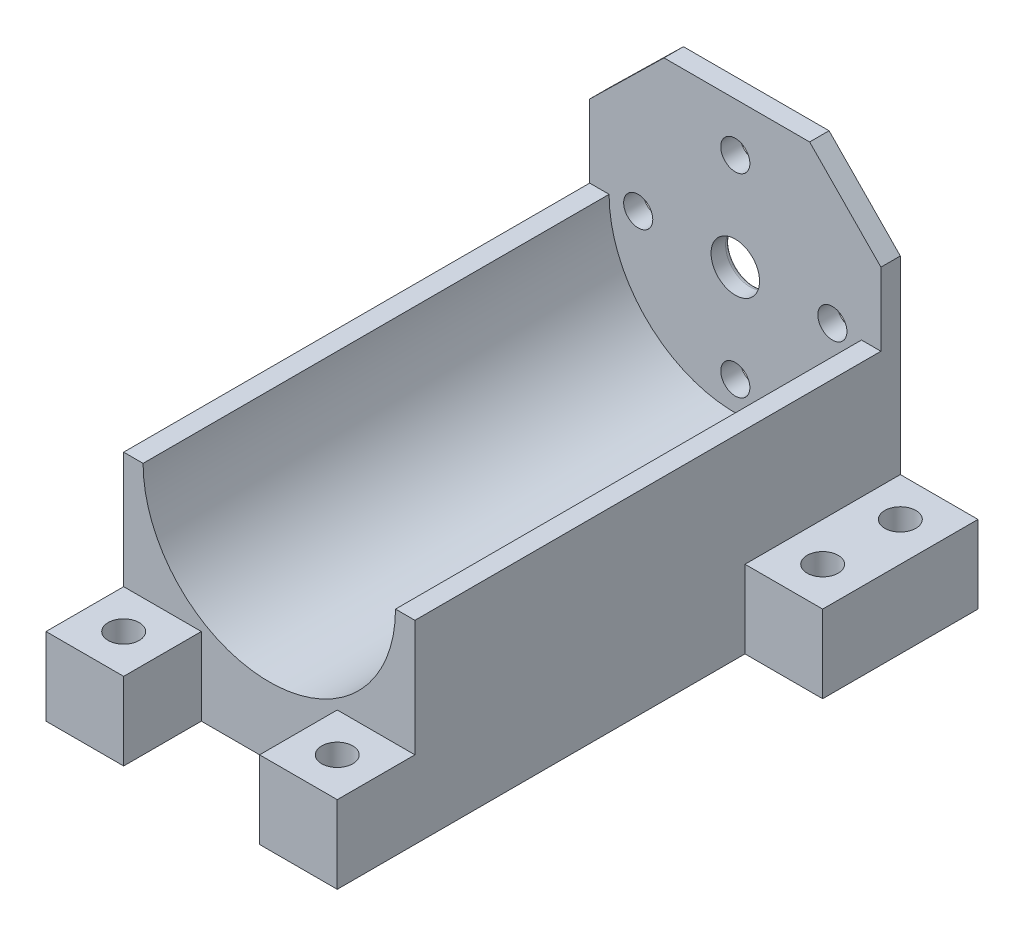
SolidWorks part; units mm, degrees
ref_plane "Plan de face" through (0, 0, 0) normal (0, 0, 1) x (1, 0, 0)
ref_plane "Plan de dessus" through (0, 0, 0) normal (0, 1, 0) x (1, 0, 0)
ref_plane "Plan de droite" through (0, 0, 0) normal (1, 0, 0) x (0, 0, -1)
sketch "Esquisse1" plane through (0, 0, 0) normal (0, 0, 1) x (1, 0, 0)
  line L0 (0, 0) -> (0, 10) construction
  line L1 (0, 0) -> (10, 0) construction
  line L2 (0, 0) -> (0, -10) construction
  line L3 (0, 0) -> (-10, 0) construction
  line L4 (-15, 0) -> (-15, 15)
  line L5 (-15, 15) -> (15, 15)
  line L6 (15, 15) -> (15, 0)
  line L7 (-15, 0) -> (-13, 0)
  line L8 (15, 0) -> (13, 0)
  line L9 (-15, 15) -> (-15, 0)
  line L10 (-15, 15) -> (0.318, 15)
  line L11 (-15, 15) -> (-15, 0)
  line L12 (-15, 7.5) -> (-15, 15)
  line L13 (-15, 15) -> (-7.341, 15)
  line L14 (-15, 7.5) -> (-7.341, 15)
  line L15 (15, 15) -> (15, 0)
  line L16 (15, 7.5) -> (15, 15)
  line L17 (0.318, 15) -> (15, 15)
  line L18 (7.659, 15) -> (15, 15)
  line L19 (7.659, 15) -> (15, 7.5)
  circle A0 centre (0, 0) radius 13
  circle A1 centre (0, 0) radius 15
  circle A2 centre (0, 10) radius 1.5
  circle A3 centre (-10, 0) radius 1.5
  circle A4 centre (10, 0) radius 1.5
  circle A5 centre (0, -10) radius 1.5
  circle A6 centre (0, 0) radius 2.5
  arc A7 (-13, 0) -> (13, 0) centre (0, 0) cw
extrude "Boss.-Extru.1" add sketch "Esquisse1" along normal blind 2 contours A0 A6 A5 A4 A3 A2 | L8 A1 L7 A0 | A1 L5 L4 | A1 L6 L5
sketch "Esquisse2" plane through (0, 0, 0) normal (0, 0, -1) x (-1, 0, 0)
  line L0 (0, 0) -> (0, -20) construction
  line L1 (0, -20) -> (15, -20)
  line L2 (15, -20) -> (15, 0)
  line L3 (0, -20) -> (-15, -20)
  line L4 (-15, -20) -> (-15, 0)
  line L5 (-15, 0) -> (-13, 0)
  line L6 (15, 0) -> (13, 0)
  line L7 (-15, 0) -> (-15, 15)
  line L8 (-15, 15) -> (15, 15)
  line L9 (15, 15) -> (15, 0)
  circle A0 centre (0, 0) radius 15
  circle A1 centre (0, 0) radius 13 construction
  circle A2 centre (0, 0) radius 13
  arc M7 (-13, 0) -> (13, 0) centre (0, 0) ccw
  line M21 (13, 0) -> (15, 0)
  line M25 (-15, 0) -> (-13, 0)
extrude "Boss.-Extru.2" add sketch "Esquisse2" against normal blind 50 contours A2 L0 A0 M21 | L0 A0 M7 M25 | L0 A0 L4 L3 | A0 L0 L1 L2
fillet "Congé1" radius 0.5 1 edges at (2.5, 0, 0)
sketch "Esquisse3" plane through (0, -20, 0) normal (0, -1, 0) x (1, 0, 0)
  line L0 (15, 0) -> (23, 0)
  line L1 (23, 0) -> (23, 8)
  line L2 (23, 8) -> (15, 8)
  line L3 (15, 50) -> (15, 0) construction
  line L4 (15, 8) -> (15, 0)
  line L5 (23, 8) -> (23, 16)
  line L6 (23, 16) -> (15, 16)
  line L7 (15, 16) -> (15, 8)
  line L8 (15, 50) -> (15, 58)
  line L9 (15, 58) -> (7, 58)
  line L10 (7, 58) -> (7, 50)
  line L11 (15, 50) -> (-15, 50) construction
  line L12 (7, 50) -> (15, 50)
  line L13 (-15, 50) -> (-15, 58)
  line L14 (-15, 58) -> (-7, 58)
  line L15 (-7, 58) -> (-7, 50)
  line L16 (-15, 58) -> (-7, 50) construction
  line L17 (-15, 50) -> (-7, 58) construction
  line L18 (7, 58) -> (15, 50) construction
  line L19 (15, 58) -> (7, 50) construction
  line L20 (15, 16) -> (23, 8) construction
  line L21 (23, 16) -> (15, 8) construction
  line L22 (15, 8) -> (23, 0) construction
  line L23 (23, 8) -> (15, 0) construction
  circle A0 centre (-11, 54) radius 1.6
  circle A1 centre (11, 54) radius 1.6
  circle A2 centre (19, 12) radius 1.6
  circle A3 centre (19, 4) radius 1.6
  line M2 (15, 0) -> (15, 50)
  line M3 (15, 50) -> (-15, 50)
extrude "Boss.-Extru.4" add sketch "Esquisse3" against normal blind 8 contours L5 L6 L2 A2 M2 | L1 L2 L0 A3 M2 | L9 L10 L8 A1 M3 | L15 L14 L13 A0 M3
